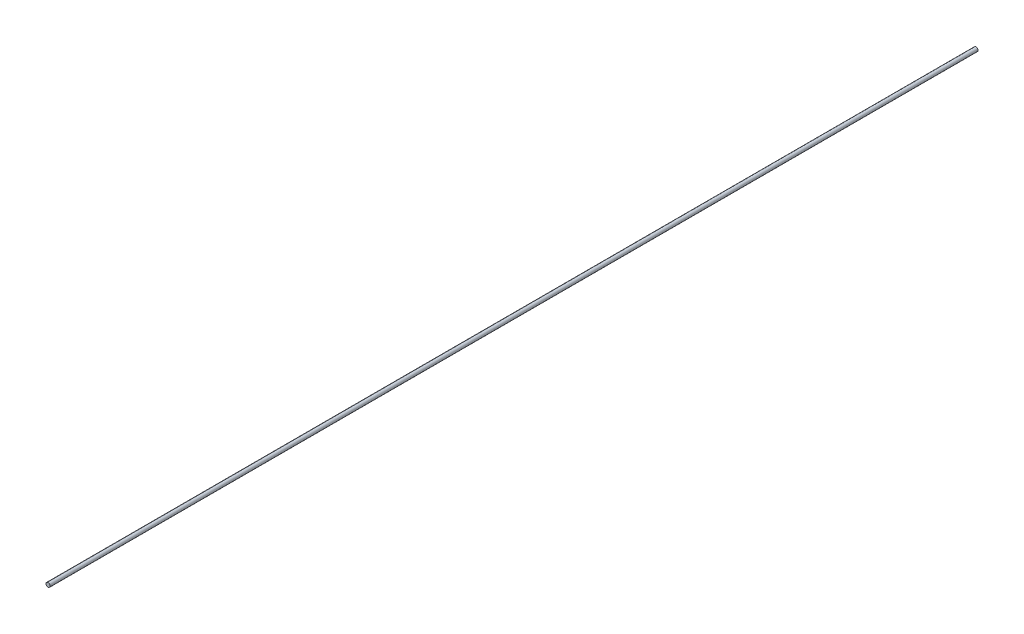
SolidWorks part; units mm, degrees
ref_plane "Front Plane" through (0, 0, 0) normal (0, 0, 1) x (1, 0, 0)
ref_plane "Top Plane" through (0, 0, 0) normal (0, 1, 0) x (1, 0, 0)
ref_plane "Right Plane" through (0, 0, 0) normal (1, 0, 0) x (0, 0, -1)
sketch "Sketch1" plane through (0, 0, 0) normal (0, 0, 1) x (1, 0, 0)
  circle A0 centre (0, 0) radius 2
  dimension "D1" = 4
extrude "Boss-Extrude1" add sketch "Sketch1" along normal blind 915
